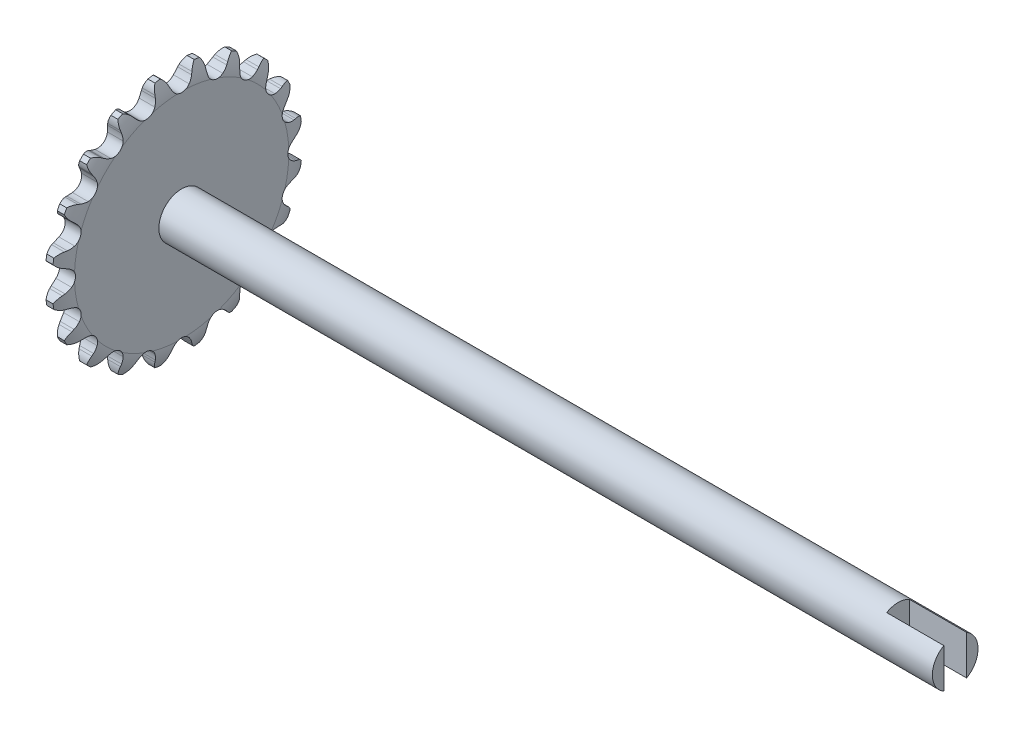
SolidWorks part; units mm, degrees
ref_plane "Plane1" through (0, 0, 0) normal (0, 0, 1) x (1, 0, 0)
ref_plane "Plane2" through (0, 0, 0) normal (0, 1, 0) x (1, 0, 0)
ref_plane "Plane3" through (0, 0, 0) normal (1, 0, 0) x (0, 0, -1)
other "Configuration Table"
sketch "Clipboard" plane through (0, 0, 0) normal (0, 1, 0) x (1, 0, 0)
  line L0 (0, 0) -> (5.967, -2.1718)
  line L1 (-15, 0) -> (100, 0) construction
  line L2 (0, 0) -> (-0.5218, 0.5897)
  line L3 (0, 0) -> (-2.9658, 1.1335)
  line L4 (0, 0) -> (2.9835, 1.0859)
  line L5 (0, 0) -> (-47.5972, -17.7524)
  line L6 (0, 0) -> (-2.3214, -1.5662)
  line L7 (-0.5218, 0.5897) -> (46.9042, 18.7948)
  line L8 (-76.2, 38.1) -> (-67.9958, 38.1)
  line L9 (-73.2057, 38.5609) -> (-73.0533, 38.5634)
  line L10 (-73.0533, 76.1892) -> (-66.6525, 76.1892)
  circle A0 centre (0, 0) radius 1.651
  circle A1 centre (0, 0) radius 16.4902
  circle A2 centre (0, 0) radius 38.1
  dimension "Dr" = 3.302
  dimension "MHD" = 32.9803
  dimension "Hub_dia" = 76.2
  dimension "Num_teeth" = 20
  dimension "Pitch" = 6.35
  dimension "Width" = 3.175
  dimension "Chamfer_wid" = 0.7874
  dimension "Chamfer_dep" = 3.175
  dimension "Overall_len" = 50.8
  dimension "Show_teeth" = 20
  dimension "Thickness" = 2.8003
  dimension "OAL" = 50.8001
  dimension "T_dim" = 8.2042
  dimension "Width_const" = 0.1524
  dimension "Width_factor" = 0.93
  dimension "Num_strands" = 1
  dimension "Transv_pitch" = 6.4008
sketch "BasProSke" plane through (0, 0, 0) normal (0, 1, 0) x (1, 0, 0)
  line L0 (-10, 0) -> (60, 0) construction
  line L1 (0, 0) -> (0, 18.7762)
  line L2 (0, 0) -> (2.8003, 0)
  line L3 (2.8003, 0) -> (2.8003, 18.7762)
  line L4 (2.0129, 21.9512) -> (0.7874, 21.9512)
  arc A0 (0, 18.7762) -> (0.7874, 21.9512) centre (6.7949, 18.7762) cw
  arc A1 (2.8003, 18.7762) -> (2.0129, 21.9512) centre (-3.9946, 18.7762) ccw
  dimension "Thickness" = 2.8003
  dimension "D1" = 6.7949
  dimension "G1" = 0.7874
  dimension "G2" = 0.7874
  dimension "H2" = 3.175
  dimension "H1" = 3.175
  dimension "Diameter" = 43.9023
revolve "Base-Revolve" add sketch "BasProSke" angle 360 about L0
sketch "GrvSke" plane through (0, 0, 0) normal (0, 1, 0) x (1, 0, 0)
  line L0 (2.8003, 18.7762) -> (2.8003, 16.4902)
  line L1 (2.8003, 16.4902) -> (6.4008, 16.4902)
  line L2 (6.4008, 16.4902) -> (6.4008, 18.7762)
  line L3 (2.0129, 21.9512) -> (7.1882, 21.9512)
  line L4 (4.6006, 0) -> (4.6006, 52.07) construction
  line L5 (-10, 0) -> (60, 0) construction
  line L6 (0, 0) -> (35.56, 0) construction
  arc A0 (6.4008, 18.7762) -> (7.1882, 21.9512) centre (13.1957, 18.7762) cw
  arc A1 (2.8003, 18.7762) -> (2.0129, 21.9512) centre (-3.9946, 18.7762) ccw
  dimension "G1" = 0.7874
  dimension "H1" = 3.175
  dimension "Diameter" = 43.9023
  dimension "Grv_diam" = 32.9803
  dimension "Grv_width" = 3.6004
  dimension "Offset" = 4.6006
revolve "Groove" [suppressed] cut sketch "GrvSke" angle 360 about L6
pattern_linear "Grooves" [suppressed]
sketch "TooCutSke" plane through (0, 0, 0) normal (1, 0, 0) x (0, 0, -1)
  line L0 (1.9183, 20.241) -> (2.0772, 20.619)
  line L1 (0, 0) -> (0, 107) construction
  line L2 (0, 20.296) -> (-10, 20.296) construction
  line L3 (-1.9183, 20.241) -> (-2.0772, 20.619)
  arc A0 (1.3375, 19.251) -> (1.9183, 20.241) centre (-2.0816, 21.9224) ccw
  arc A1 (1.3375, 19.251) -> (-1.3375, 19.251) centre (0, 20.296) cw
  arc A2 (2.0772, 20.619) -> (4.5659, 22.2725) centre (4.5659, 19.5729) cw
  arc A3 (-1.3375, 19.251) -> (-1.9183, 20.241) centre (2.0816, 21.9224) cw
  arc A4 (-2.0772, 20.619) -> (-4.5659, 22.2725) centre (-4.5659, 19.5729) ccw
  arc A5 (4.5659, 22.2725) -> (-4.5659, 22.2725) centre (0, 0) ccw
  dimension "R" = 1.6974
  dimension "E" = 4.339
  dimension "F" = 2.6996
  dimension "Pitch_radius" = 20.296
  dimension "W" = 4.5659
  dimension "V" = 0.7232
  dimension "A" = 38
  dimension "B" = 15.2
extrude "ToothCut" cut sketch "TooCutSke" along normal through all
pattern_circular "TeethCuts" count 20 every 18 about axis through (-10, 0, 0) along (1, 0, 0) of "ToothCut"
sketch "HubNeaOneSke" plane through (0, 0, 0) normal (-1, 0, 0) x (0, 0, 1)
  circle A0 centre (0, 0) radius 16.4902
  dimension "Diameter" = 32.9803
extrude "HubNearOne" [suppressed] add sketch "HubNeaOneSke" along normal blind 47.9997
sketch "HubNeaBotSke" plane through (0, 0, 0) normal (-1, 0, 0) x (0, 0, 1)
  circle A0 centre (0, 0) radius 16.4902
  dimension "Diameter" = 32.9803
extrude "HubNearBoth" [suppressed] add sketch "HubNeaBotSke" along normal blind 23.9999
ref_plane "FarPln" through (2.8003, 0, 0) normal (1, 0, 0) x (0, 0, -1)
sketch "HubFarSke" plane through (2.8003, 0, 0) normal (1, 0, 0) x (0, 0, -1)
  circle A0 centre (0, 0) radius 16.4902
  dimension "Diameter" = 32.9803
extrude "HubFar" [suppressed] add sketch "HubFarSke" along normal blind 23.9999
sketch "BorSke" plane through (0, 0, 0) normal (1, 0, 0) x (0, 0, -1)
  circle A0 centre (0, 0) radius 4
  dimension "Diameter" = 8
extrude "Bore" cut sketch "BorSke" along normal mid plane 101.6001
sketch "KeySke" plane through (0, 0, 0) normal (1, 0, 0) x (0, 0, -1)
  line L0 (-0.127, 0) -> (-0.127, 4.2042)
  line L1 (-0.127, 4.2042) -> (0.127, 4.2042)
  line L2 (0.127, 4.2042) -> (0.127, 0)
  line L3 (0, 0) -> (0, 34) construction
  line L4 (-0.127, 0) -> (0.127, 0)
  dimension "Offset" = 4.2042
  dimension "Width" = 0.254
extrude "Keyway" [suppressed] cut sketch "KeySke" along normal mid plane 101.6001
pattern_circular "Keyway2" [suppressed] count 2 every 90 about axis through (-10, 0, 0) along (1, 0, 0)
sketch "Sketch1" plane through (0, 0, 0) normal (-1, 0, 0) x (0, 0, 1)
  circle A0 centre (0, 0) radius 4 construction
  circle A1 centre (0, 0) radius 4
extrude "Boss-Extrude1" add sketch "Sketch1" against normal blind 201
ref_plane "Plane4" through (128.3004, 0, 0) normal (1, 0, 0) x (0, 0, -1)
split "Split1" trim tools "Plane4" bodies to split 105 resulting bodies 107
sketch "Sketch3" plane through (128.3004, 0, 0) normal (1, 0, 0) x (0, 0, -1)
  line L2 (2, 3.4641) -> (2, -3.4641)
  line L3 (-2, -3.4641) -> (-2, 3.4641)
  arc A0 (2, 3.4641) -> (-2, 3.4641) centre (0, 0) ccw construction
  arc A3 (-2, 3.4641) -> (-2, -3.4641) centre (0, 0) ccw
  arc A4 (-2, -3.4641) -> (2, -3.4641) centre (0, 0) ccw construction
  arc A5 (2, -3.4641) -> (2, 3.4641) centre (0, 0) ccw
  dimension "D1" = 8
  dimension "D2" = 2
  dimension "D3" = 2
extrude "Boss-Extrude2" add sketch "Sketch3" along normal blind 10
equation "\"Num_teeth@Clipboard\" = int( \"Num_teeth@Clipboard\" )"
equation "\"Num_teeth@Clipboard\" = ((sgn( \"Num_teeth@Clipboard\" - 5.0)+1)*( \"Num_teeth@Clipboard\" - 5.0))/2 +5.0"
equation "\"Num_teeth@Clipboard\" = ((sgn( \"Num_teeth@Clipboard\" - 200.0)-1)*( \"Num_teeth@Clipboard\" - 200.0))/-2 +200.0"
equation "\"MHD@Clipboard\" = \"Pitch@Clipboard\" * (1.0 / tan(3.14159265 / \"Num_teeth@Clipboard\" ) - 1.0) - 0.03"
equation "\"Thickness@Clipboard\"  = \"Width@Clipboard\" * \"Width_factor@Clipboard\" - \"Width_const@Clipboard\" + (\"Num_strands@Clipboard\" - 1) * \"Transv_pitch@Clipboard\""
equation "\"OAL@Clipboard\" = \"Thickness@Clipboard\""
equation "\"MHD@Clipboard\" = ((sgn( \"MHD@Clipboard\" - \"Hub_dia@Clipboard\" )-1)*( \"MHD@Clipboard\" - \"Hub_dia@Clipboard\" ))/-2+ \"Hub_dia@Clipboard\""
equation "\"OAL@Clipboard\" = ((sgn( \"OAL@Clipboard\" - \"Overall_len@Clipboard\" )+1)*( \"OAL@Clipboard\" - \"Overall_len@Clipboard\" ))/2 + \"Overall_len@Clipboard\" + 0.000002"
equation "\"Num_teeth@TeethCuts\" = int( \"Show_teeth@Clipboard\" ) + 1"
equation "\"Num_teeth@TeethCuts\" = ((sgn( \"Num_teeth@TeethCuts\" - \"Num_teeth@Clipboard\" )-1)*( \"Num_teeth@TeethCuts\" - \"Num_teeth@Clipboard\" ))/-2+ \"Num_teeth@Clipboard\""
equation "\"Num_teeth@TeethCuts\" = ((sgn( \"Num_teeth@TeethCuts\" - 2.0)+1)*( \"Num_teeth@TeethCuts\" - 2.0))/2 +2.0"
equation "\"Angle@TeethCuts\" = 360.0 / \"Num_teeth@Clipboard\""
equation "\"Pitch_radius@TooCutSke\" = ( \"Pitch@Clipboard\" / 2.0) / sin(3.14159265 / \"Num_teeth@Clipboard\" )  'ma"
equation "\"R@TooCutSke\"  = \"Dr@Clipboard\" * 0.5025 + 0.0015"
equation "\"A@TooCutSke\" = 35.0 + (60.0 / \"Num_teeth@Clipboard\")"
equation "\"E@TooCutSke\"  = \"Dr@Clipboard\" * 1.3025 + 0.0015"
equation "\"B@TooCutSke\"  = 18.0 - (56.0 / \"Num_teeth@Clipboard\" )"
equation "\"W@TooCutSke\" = 1.4 * \"Dr@Clipboard\" * cos(3.14159265 / \"Num_teeth@Clipboard\" )"
equation "\"V@TooCutSke\" = 1.4 * \"Dr@Clipboard\" * sin(3.14159265 / \"Num_teeth@Clipboard\" )"
equation "\"Diameter@BasProSke\" = 2.0 * ( (0.3 * \"Pitch@Clipboard\" ) +  \"Pitch@Clipboard\" / 2.0 / tan(3.14159265 / \"Num_teeth@Clipboard\" ))"
equation "\"Thickness@BasProSke\"  = \"Thickness@Clipboard\""
equation "\"G1@BasProSke\" =  \"Chamfer_wid@Clipboard\""
equation "\"G2@BasProSke\" =  \"Chamfer_wid@Clipboard\""
equation "\"H1@BasProSke\" =  \"Chamfer_dep@Clipboard\""
equation "\"H2@BasProSke\" =  \"Chamfer_dep@Clipboard\""
equation "\"Diameter@GrvSke\" = \"Diameter@BasProSke\""
equation "\"G1@GrvSke\" = \"Chamfer_wid@Clipboard\""
equation "\"H1@GrvSke\" = \"Chamfer_dep@Clipboard\""
equation "\"Grv_diam@GrvSke\" =  \"Pitch@Clipboard\" * (1.0 / tan(3.14159265 / \"Num_teeth@Clipboard\" ) - 1.0) - 0.03"
equation "\"Grv_width@GrvSke\" =  \"Transv_pitch@Clipboard\" - ( \"Width@Clipboard\" * \"Width_factor@Clipboard\" - \"Width_const@Clipboard\" )"
equation "\"Offset@GrvSke\" = \"Grv_width@GrvSke\" / 2.0 + ( \"Width@Clipboard\" * \"Width_factor@Clipboard\" - \"Width_const@Clipboard\" )"
equation "\"Offset@Grooves\" = \"Transv_pitch@Clipboard\""
equation "\"Num_grvs@Grooves\" = \"Num_strands@Clipboard\""
equation "\"Num_grvs@Grooves\" = \"Num_grvs@Grooves\" - 1 * sgn( \"Num_grvs@Grooves\" -1)"
equation "\"Diameter@HubNeaOneSke\" = \"MHD@Clipboard\""
equation "\"Length@HubNearOne\" = \"OAL@Clipboard\" - \"Thickness@BasProSke\""
equation "\"Diameter@HubNeaBotSke\" = \"MHD@Clipboard\""
equation "\"Length@HubNearBoth\" = ( \"OAL@Clipboard\" - \"Thickness@BasProSke\" ) / 2.0"
equation "\"Thickness@FarPln\" = \"Thickness@BasProSke\""
equation "\"Diameter@HubFarSke\" = \"MHD@Clipboard\""
equation "\"Length@HubFar\" = ( \"OAL@Clipboard\" - \"Thickness@BasProSke\" ) / 2.0"
equation "\"D1@Bore\" = \"OAL@Clipboard\" * 2.0"
equation "\"D1@Keyway\" = \"OAL@Clipboard\" * 2.0"
equation "\"Offset@KeySke\" = \"T_dim@Clipboard\" - \"Diameter@BorSke\" / 2.0"
